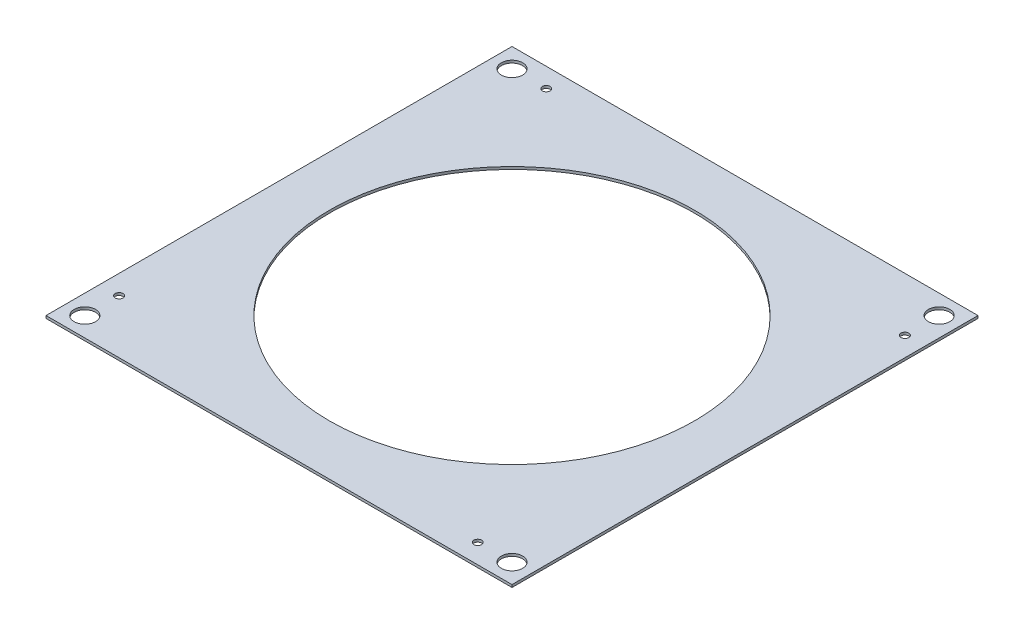
SolidWorks part; units mm, degrees
ref_plane "Front Plane" through (0, 0, 0) normal (0, 0, 1) x (1, 0, 0)
ref_plane "Top Plane" through (0, 0, 0) normal (0, 1, 0) x (1, 0, 0)
ref_plane "Right Plane" through (0, 0, 0) normal (1, 0, 0) x (0, 0, -1)
sketch "Sketch1" plane through (0, 0, 0) normal (0, 1, 0) x (1, 0, 0)
  line L1 (-76.2, -76.2) -> (76.2, -76.2)
  line L2 (-76.2, -76.2) -> (-76.2, 76.2)
  line L3 (-76.2, 76.2) -> (76.2, 76.2)
  line L4 (76.2, -76.2) -> (76.2, 76.2)
  line L5 (-76.2, -76.2) -> (76.2, 76.2) construction
  line L6 (-76.2, 76.2) -> (76.2, -76.2) construction
  circle A0 centre (0, 0) radius 59.69
  dimension "D1" = 119.38
  dimension "D2" = 152.4
  dimension "D3" = 152.4
extrude "Boss-Extrude1" add sketch "Sketch1" along normal mid plane 0.8382
sketch "Sketch2" plane through (0, 0.4191, 0) normal (0, 1, 0) x (1, 0, 0)
  line L0 (-76.2, 76.2) -> (-76.2, -76.2) construction
  line L1 (76.2, 76.2) -> (-76.2, 76.2) construction
  circle A0 centre (-69.85, 69.85) radius 3.4925
  circle A1 centre (-58.6472, 69.85) radius 1.27
  dimension "D1" = 6.985
  dimension "D4" = 2.54
  dimension "D2" = 6.35
  dimension "D3" = 6.35
extrude "Cut-Extrude1" cut sketch "Sketch2" against normal through all
pattern_circular "CirPattern1" count 4 over 360 about axis through (0, 0, 0) along (0, 1, 0) of "Cut-Extrude1"
